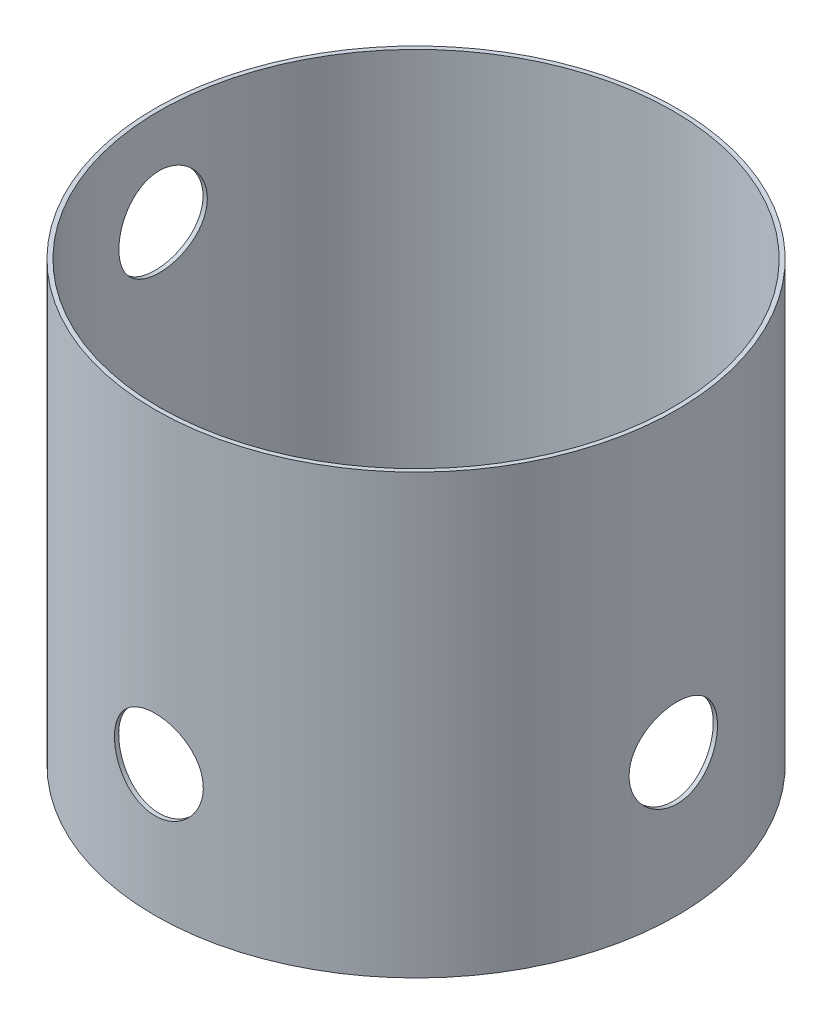
SolidWorks part; units mm, degrees
ref_plane "Front Plane" through (0, 0, 0) normal (0, 0, 1) x (1, 0, 0)
ref_plane "Top Plane" through (0, 0, 0) normal (0, 1, 0) x (1, 0, 0)
ref_plane "Right Plane" through (0, 0, 0) normal (1, 0, 0) x (0, 0, -1)
sketch "Sketch2" plane through (0, 0, 0) normal (0, 1, 0) x (-1, 0, 0)
  circle A0 centre (4.0786, 4.7536) radius 62.854
  circle A2 centre (4.0786, 4.7536) radius 61.838
  dimension "D1" = 1.016
extrude "Boss-Extrude1" add sketch "Sketch2" along normal blind 105.5
extrude "Cut-Extrude1" cut sketch "Sketch3" against normal blind 105.5
sketch "Sketch3" plane through (-8.0809, 23.5999, 4.7536) normal (0, 0, -1) x (-1, 0, 0)
  circle A0 centre (-4.0023, 7.9001) radius 10.7
extrude "Cut-Extrude2" cut sketch "Sketch4" along normal blind 105.5
sketch "Sketch4" plane through (-4.0786, 23.5999, 9.5717) normal (1, 0, 0) x (0, 0, -1)
  circle A0 centre (4.8181, 10.3501) radius 10.65
extrude "Cut-Extrude3" cut sketch "Sketch5" against normal blind 105.5
sketch "Sketch5" plane through (-4.0786, 23.5999, 9.5717) normal (1, 0, 0) x (0, 0, -1)
  circle A0 centre (4.8181, 58.7501) radius 10.65
